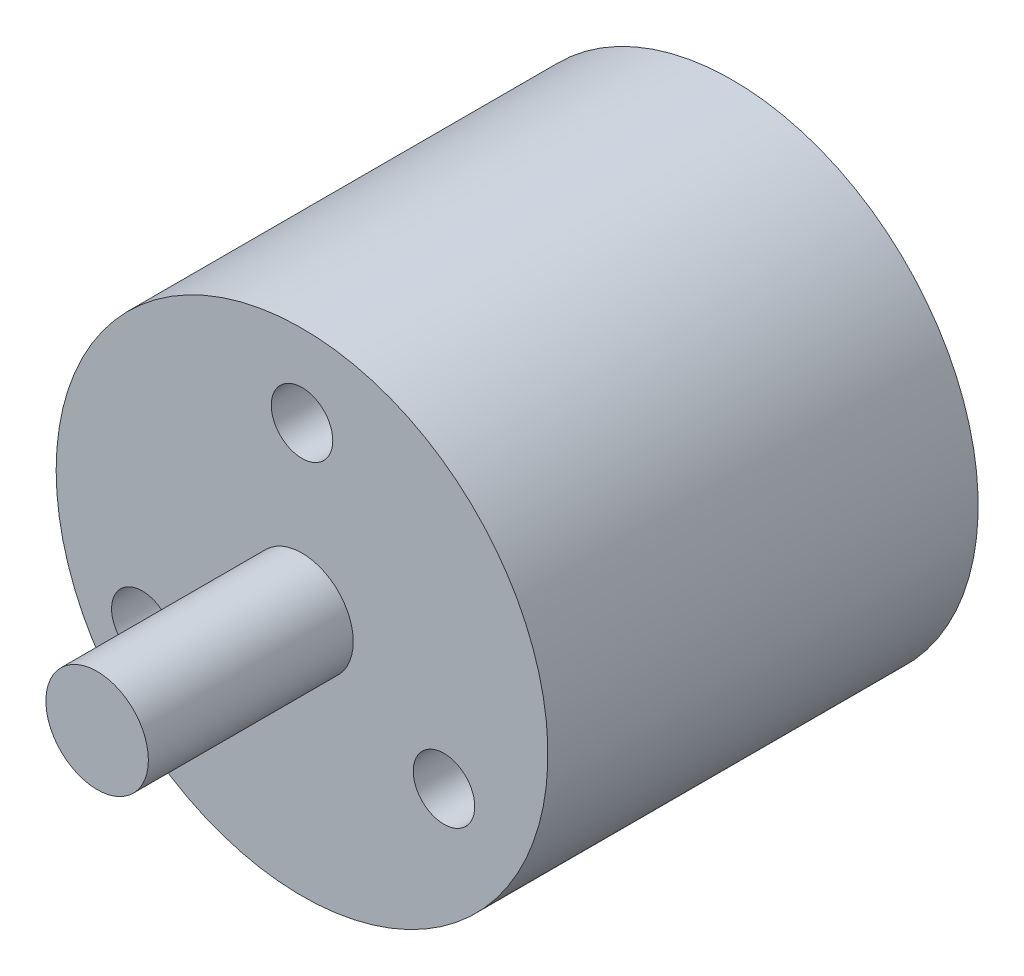
SolidWorks part; units mm, degrees
ref_plane "Plan de face" through (0, 0, 0) normal (0, 0, 1) x (1, 0, 0)
ref_plane "Plan de dessus" through (0, 0, 0) normal (0, 1, 0) x (1, 0, 0)
ref_plane "Plan de droite" through (0, 0, 0) normal (1, 0, 0) x (0, 0, -1)
sketch "Esquisse1" plane through (0, 0, 0) normal (0, 0, 1) x (1, 0, 0)
  circle A0 centre (0, 0) radius 12
  dimension "D1" = 24
extrude "Boss.-Extru.1" add sketch "Esquisse1" along normal blind 21
sketch "Esquisse2" plane through (0, 0, 21) normal (0, 0, 1) x (1, 0, 0)
  circle A0 centre (0, 0) radius 2.5
  dimension "D1" = 5
extrude "Boss.-Extru.2" add sketch "Esquisse2" along normal blind 10
sketch "Esquisse3" plane through (0, 0, 21) normal (0, 0, 1) x (1, 0, 0)
  line L0 (0, 8) -> (0, 0) construction
  line L1 (0, 0) -> (-7.7942, -4.5) construction
  line L2 (0, 0) -> (6.9282, -4) construction
  circle A0 centre (0, 8) radius 1.5
  circle A1 centre (-7.7942, -4.5) radius 1.5016
  circle A2 centre (6.9282, -4) radius 1.5
  dimension "D1" = 3
  dimension "D3" = 3.0033
  dimension "D5" = 3
  dimension "D2" = 8
  dimension "D4" = 9
  dimension "D6" = 8
  dimension "D7" = 120
  dimension "D8" = 120
extrude "Enlèv. mat.-Extru.1" cut sketch "Esquisse3" against normal blind 4
